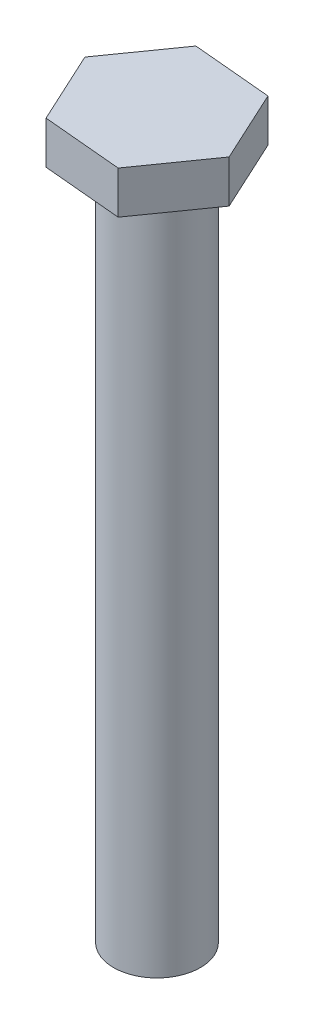
SolidWorks part; units mm, degrees
ref_plane "Front Plane" through (0, 0, 0) normal (0, 0, 1) x (1, 0, 0)
ref_plane "Top Plane" through (0, 0, 0) normal (0, 1, 0) x (1, 0, 0)
ref_plane "Right Plane" through (0, 0, 0) normal (1, 0, 0) x (0, 0, -1)
sketch "Sketch2" plane through (0, 0, 0) normal (0, 1, 0) x (1, 0, 0)
  circle A0 centre (0, 0) radius 2.55
  dimension "D1" = 5.1
extrude "Boss-Extrude1" add sketch "Sketch2" against normal blind 40
sketch "Sketch3" plane through (0, 0, 0) normal (0, 1, 0) x (1, 0, 0)
  line L1 (2.695, 3.8219) -> (-1.9623, 4.2449)
  line L2 (-1.9623, 4.2449) -> (-4.6574, 0.423)
  line L3 (-4.6574, 0.423) -> (-2.695, -3.8219)
  line L4 (-2.695, -3.8219) -> (1.9623, -4.2449)
  line L5 (1.9623, -4.2449) -> (4.6574, -0.423)
  line L6 (4.6574, -0.423) -> (2.695, 3.8219)
  circle A0 centre (0, 0) radius 4.05 construction
  dimension "D1" = 8.1
extrude "Boss-Extrude2" add sketch "Sketch3" along normal blind 2.5
